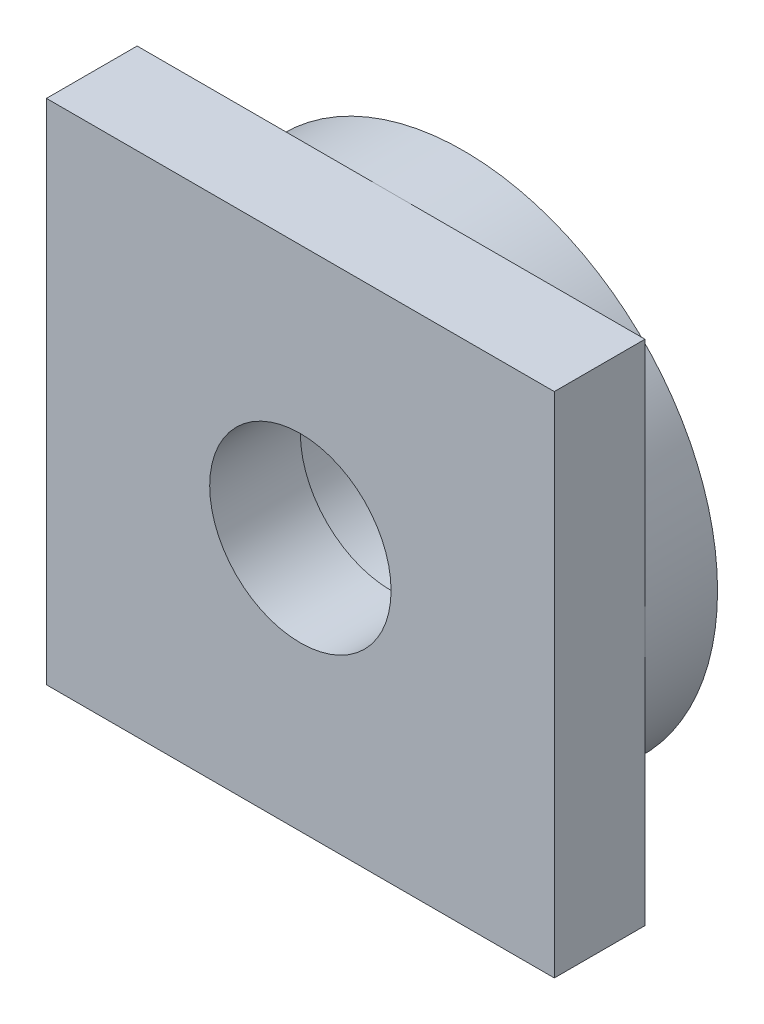
SolidWorks part; units mm, degrees
ref_plane "Ön Düzlem" through (0, 0, 0) normal (0, 0, 1) x (1, 0, 0)
ref_plane "Üst Düzlem" through (0, 0, 0) normal (0, 1, 0) x (1, 0, 0)
ref_plane "Sağ Düzlem" through (0, 0, 0) normal (1, 0, 0) x (0, 0, -1)
sketch "Sketch1" plane through (0, 0, 0) normal (0, 0, 1) x (1, 0, 0)
  circle A0 centre (0, 0) radius 18
  circle A1 centre (0, 0) radius 28
  dimension "D1" = 36
  dimension "D2" = 10
extrude "Boss-Extrude1" add sketch "Sketch1" along normal blind 22
sketch "Sketch2" plane through (0, 0, 22) normal (0, 0, 1) x (1, 0, 0)
  line L1 (-28, -28) -> (28, -28)
  line L2 (-28, -28) -> (-28, 28)
  line L3 (-28, 28) -> (28, 28)
  line L4 (28, -28) -> (28, 28)
  line L5 (-28, -28) -> (28, 28) construction
  line L6 (-28, 28) -> (28, -28) construction
  point P0 (0, 0)
  dimension "D1" = 56
  dimension "D2" = 56
extrude "Boss-Extrude2" add sketch "Sketch2" along normal blind 10
sketch "Sketch3" plane through (0, 0, 0) normal (0, 0, -1) x (-1, 0, 0)
  line L0 (0, 0) -> (-28, -28)
  line L1 (-28, -28) -> (-28, 0) construction
  line L2 (0, 0) -> (28, -28)
  line L3 (28, -28) -> (-28, -28)
extrude "Cut-Extrude1" cut sketch "Sketch3" against normal blind 14
sketch "Sketch4" plane through (0, 0, 22) normal (0, 0, -1) x (-1, 0, 0)
  circle A0 centre (0, 0) radius 5
  dimension "D1" = 10
extrude "Cut-Extrude2" cut sketch "Sketch4" against normal blind 14
sketch "Sketch5" plane through (0, 0, 22) normal (0, 0, -1) x (-1, 0, 0)
  circle A0 centre (0, 0) radius 21.225
  circle A1 centre (0, 0) radius 11
  dimension "D1" = 22
extrude "Boss-Extrude3" add sketch "Sketch5" along normal blind 8
sketch "Sketch6" plane through (0, 0, 0) normal (0, 0, -1) x (-1, 0, 0)
  circle A0 centre (0, 0) radius 50.3917
extrude "Cut-Extrude3" cut sketch "Sketch6" against normal up to surface (14 mm away) up to face at (0, -10.6317, 14)
sketch "Sketch9" plane through (0, 0, 32) normal (0, 0, 1) x (1, 0, 0)
  circle A0 centre (0, 0) radius 10
  dimension "D1" = 20
extrude "Cut-Extrude6" cut sketch "Sketch9" against normal up to surface (10 mm away) up to face at (-5, 0, 22)
